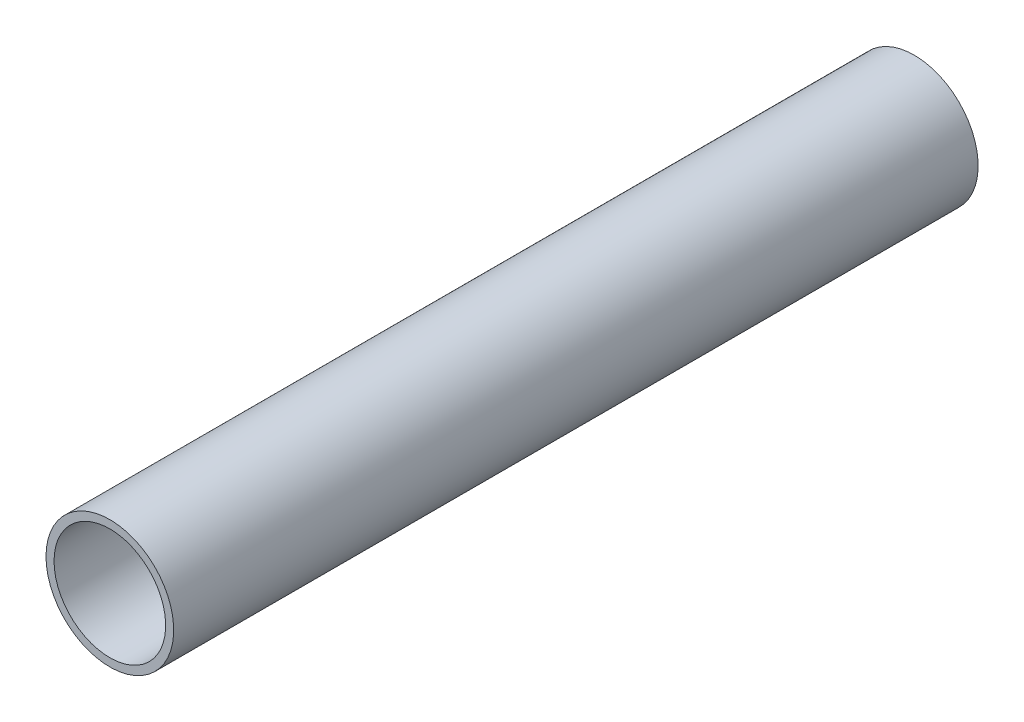
SolidWorks part; units mm, degrees
ref_plane "Alzado" through (0, 0, 0) normal (0, 0, 1) x (1, 0, 0)
ref_plane "Planta" through (0, 0, 0) normal (0, 1, 0) x (1, 0, 0)
ref_plane "Vista lateral" through (0, 0, 0) normal (1, 0, 0) x (0, 0, -1)
sketch "Croquis1" plane through (0, 0, 0) normal (0, 0, 1) x (1, 0, 0)
  circle A0 centre (0, 0) radius 7.9375
  circle A1 centre (0, 0) radius 6.9375
  dimension "D1" = 15.875
  dimension "D2" = 1
extrude "Saliente-Extruir1" add sketch "Croquis1" along normal mid plane 100
